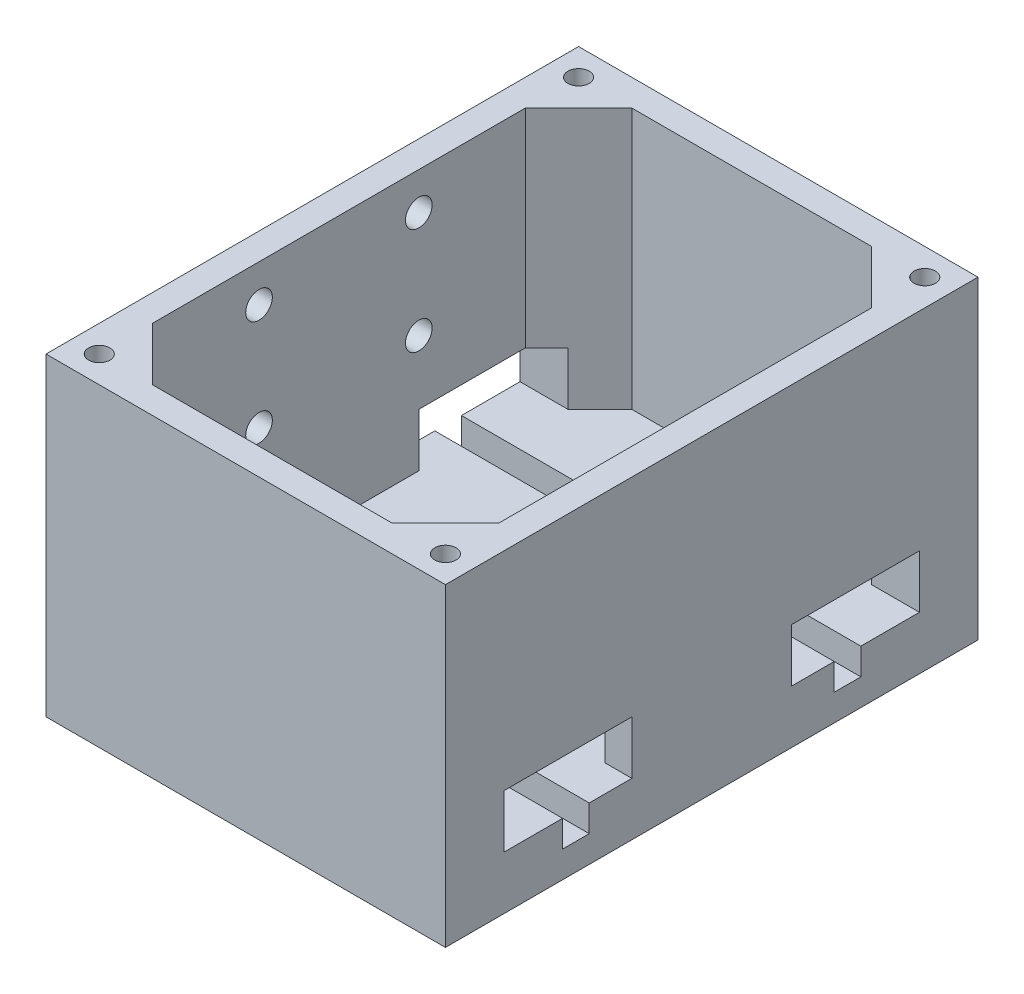
SolidWorks part; units mm, degrees
ref_plane "Front Plane" through (0, 0, 0) normal (0, 0, 1) x (1, 0, 0)
ref_plane "Top Plane" through (0, 0, 0) normal (0, 1, 0) x (1, 0, 0)
ref_plane "Right Plane" through (0, 0, 0) normal (1, 0, 0) x (0, 0, -1)
sketch "Sketch1" plane through (0, 0, 0) normal (0, 1, 0) x (1, 0, 0)
  line L1 (37.5, -50) -> (-37.5, -50)
  line L2 (37.5, -50) -> (37.5, 50)
  line L3 (37.5, 50) -> (-37.5, 50)
  line L4 (-37.5, -50) -> (-37.5, 50)
  line L5 (37.5, -50) -> (-37.5, 50) construction
  line L6 (37.5, 50) -> (-37.5, -50) construction
  point P0 (0, 0)
  dimension "D1" = 75
  dimension "D2" = 100
extrude "Boss-Extrude1" add sketch "Sketch1" along normal blind 10
sketch "Sketch2" plane through (0, 10, 0) normal (0, 1, 0) x (1, 0, 0)
  circle A0 centre (0, 0) radius 5
  circle A1 centre (0, 0) radius 19 construction
  dimension "D1" = 10
  dimension "D2" = 38
extrude "Boss-Extrude2" add sketch "Sketch2" along normal blind 5
sketch "Sketch3" plane through (0, 10, 0) normal (0, 1, 0) x (1, 0, 0)
  line L0 (37.5, -50) -> (37.5, 50) construction
  line L1 (-37.5, -23) -> (37.5, -23)
  line L2 (-37.5, -23) -> (-37.5, -28)
  line L3 (-37.5, -28) -> (37.5, -28)
  line L4 (37.5, -23) -> (37.5, -28)
  line L5 (-37.5, 50) -> (-37.5, -50) construction
  line L6 (-37.5, -50) -> (37.5, -50) construction
  line L7 (37.5, 50) -> (-37.5, 50) construction
  line L8 (-37.5, 28) -> (37.5, 28)
  line L9 (-37.5, 28) -> (-37.5, 23)
  line L10 (-37.5, 23) -> (37.5, 23)
  line L11 (37.5, 28) -> (37.5, 23)
  dimension "D1" = 22
  dimension "D2" = 5
  dimension "D3" = 22
extrude "Cut-Extrude1" cut sketch "Sketch3" against normal blind 5
sketch "Sketch4" plane through (0, 10, 0) normal (0, 1, 0) x (1, 0, 0)
  line L0 (-37.5, 50) -> (37.5, 50)
  line L1 (37.5, 50) -> (37.5, -50)
  line L2 (37.5, -50) -> (-37.5, -50)
  line L3 (-37.5, -50) -> (-37.5, 50)
  line L4 (-32.5, 45) -> (32.5, 45)
  line L5 (32.5, 45) -> (32.5, -45)
  line L6 (32.5, -45) -> (-32.5, -45)
  line L7 (-32.5, -45) -> (-32.5, 45)
  dimension "D1" = 5
extrude "Boss-Extrude3" add sketch "Sketch4" along normal up to vertex (49 mm away)
sketch "Sketch5" plane through (-37.5, 0, 0) normal (-1, 0, 0) x (0, 0, 1)
  line L1 (15, 10) -> (39, 10)
  line L2 (15, 10) -> (15, 20)
  line L3 (15, 20) -> (39, 20)
  line L4 (39, 10) -> (39, 20)
  line L5 (23, 10) -> (28, 10) construction
  line L6 (28, 5) -> (28, 10) construction
  line L7 (-39, 10) -> (-15, 10)
  line L8 (-39, 10) -> (-39, 20)
  line L9 (-39, 20) -> (-15, 20)
  line L10 (-15, 10) -> (-15, 20)
  line L11 (-28, 5) -> (-28, 10) construction
  line L12 (-28, 10) -> (-23, 10) construction
  dimension "D1" = 24
  dimension "D2" = 10
  dimension "D3" = 11
  dimension "D4" = 11
extrude "Cut-Extrude2" cut sketch "Sketch5" against normal up to surface (75 mm away) up to face at (37.5, 29.5, 0)
chamfer "Chamfer1" distance 10 angle 45 4 edges at (32.5, 34.5, 45) (-32.5, 34.5, 45) (-32.5, 34.5, -45) (32.5, 34.5, -45)
sketch "Sketch6" plane through (0, 59, 0) normal (0, 1, 0) x (1, 0, 0)
  line L0 (-37.5, 50) -> (-27.5, 40) construction
  line L1 (-32.5, 35) -> (-22.5, 45) construction
  line L2 (0, -37.95) -> (0, 37.95) construction
  line L3 (-37.95, 0) -> (37.95, 0) construction
  circle A0 centre (-32.5, 45) radius 2
  circle A1 centre (32.5, 45) radius 2
  circle A2 centre (32.5, -45) radius 2
  circle A3 centre (-32.5, -45) radius 2
  dimension "D1" = 4
extrude "Cut-Extrude3" cut sketch "Sketch6" against normal blind 10
sketch "Sketch8" plane through (-37.5, 0, 0) normal (-1, 0, 0) x (0, 0, 1)
  circle A0 centre (-15, 52) radius 2.5
  circle A2 centre (15, 52) radius 2.5
  circle A4 centre (-15, 32) radius 2.5
  circle A5 centre (15, 32) radius 2.5
  point P12 (0, 0)
  point P13 (0, 0)
  point P14 (0, 0)
  dimension "D1" = 5
  dimension "D2" = 20
extrude "Cut-Extrude4" cut sketch "Sketch8" against normal blind 20
sketch "Sketch9" plane through (0, 10, 0) normal (0, 1, 0) x (1, 0, 0)
  line L0 (0, 0) -> (0, 50) construction
  line L1 (37.5, 28) -> (-37.5, 28) construction
  line L2 (3, 36) -> (8, 36)
  line L3 (3, 36) -> (3, 31)
  line L4 (3, 31) -> (8, 31)
  line L5 (8, 36) -> (8, 31)
  line L6 (-37.5, -28) -> (37.5, -28) construction
  line L7 (-8, -31) -> (-3, -31)
  line L8 (-8, -31) -> (-8, -36)
  line L9 (-8, -36) -> (-3, -36)
  line L10 (-3, -31) -> (-3, -36)
  line L11 (37.5, 50) -> (-37.5, 50) construction
  dimension "D1" = 5
  dimension "D2" = 5
  dimension "D3" = 3
  dimension "D4" = 3
  dimension "D5" = 5
  dimension "D6" = 5
  dimension "D7" = 3
  dimension "D8" = 3
extrude "Boss-Extrude5" add sketch "Sketch9" along normal blind 10
